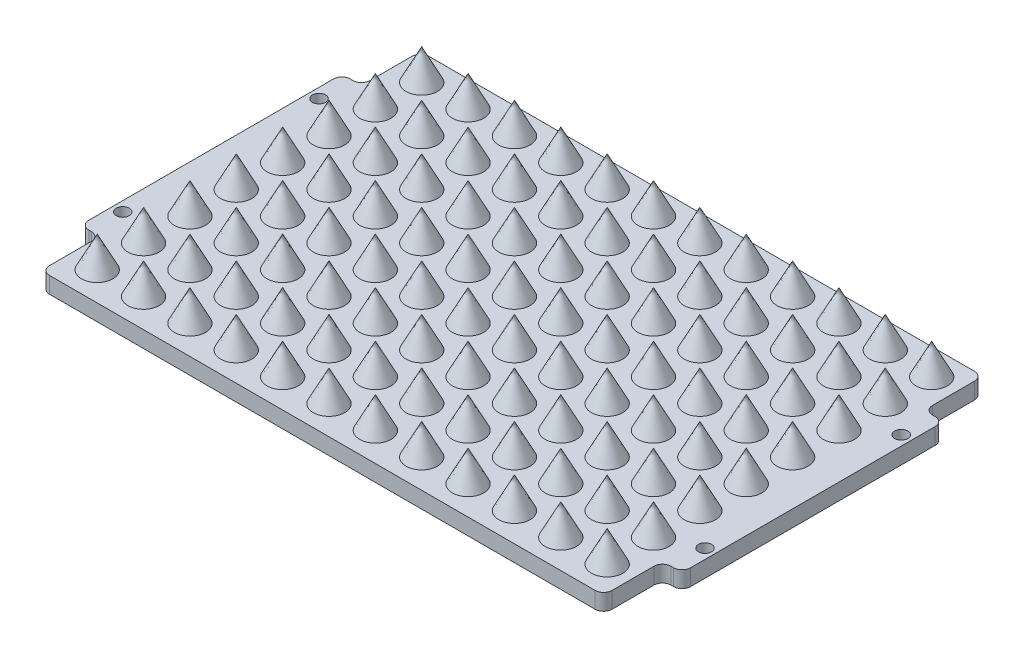
SolidWorks part; units mm, degrees
ref_plane "Front Plane" through (0, 0, 0) normal (0, 0, 1) x (1, 0, 0)
ref_plane "Top Plane" through (0, 0, 0) normal (0, 1, 0) x (1, 0, 0)
ref_plane "Right Plane" through (0, 0, 0) normal (1, 0, 0) x (0, 0, -1)
sketch "Sketch1" plane through (0, 0, 0) normal (0, 1, 0) x (1, 0, 0)
  line L1 (-54.61, -36.83) -> (54.61, -36.83)
  line L2 (-54.61, -36.83) -> (-54.61, 36.83)
  line L3 (-54.61, 36.83) -> (54.61, 36.83)
  line L4 (54.61, -36.83) -> (54.61, 36.83)
  line L5 (-54.61, -36.83) -> (54.61, 36.83) construction
  line L6 (-54.61, 36.83) -> (54.61, -36.83) construction
  point P0 (0, 0)
  dimension "D1" = 109.22
  dimension "D2" = 73.66
extrude "Boss-Extrude1" add sketch "Sketch1" against normal blind 3.175
ref_plane "Plane1" through (0, 0, -31.75) normal (0, 0, 1) x (1, 0, 0)
sketch "Sketch2" plane through (0, 0, -31.75) normal (0, 0, 1) x (1, 0, 0)
  line L0 (-52.324, 0) -> (-49.276, 6)
  line L3 (-49.276, 0) -> (-52.324, 0)
  line L4 (-49.276, 6) -> (-49.276, 0)
  point P5 (-50.8, 0)
  dimension "D1" = 3.048
  dimension "D3" = 50.8
revolve "Revolve3" add sketch "Sketch2" angle 360 about L4
pattern_linear "LPattern1" count 12 spacing 9 along (1, 0, 0) count 8 spacing 9 along (0, 0, 1) of "Revolve3"
sketch "Sketch3" plane through (0, 0, 0) normal (0, 1, 0) x (1, 0, 0)
  line L0 (-54.61, 36.83) -> (-54.61, -36.83) construction
  line L1 (-54.61, 25.4) -> (-58.42, 25.4)
  line L2 (-54.61, 25.4) -> (-54.61, -25.4)
  line L3 (-54.61, -25.4) -> (-58.42, -25.4)
  line L4 (-58.42, 25.4) -> (-58.42, -25.4)
  line L5 (0, 0) -> (0, 36.83) construction
  line L6 (54.61, 36.83) -> (-54.61, 36.83) construction
  line L7 (58.42, 25.4) -> (58.42, -25.4)
  line L8 (54.61, -25.4) -> (58.42, -25.4)
  line L9 (54.61, 25.4) -> (54.61, -25.4)
  line L10 (54.61, 25.4) -> (58.42, 25.4)
  circle A0 centre (-56.515, 19.05) radius 1.27
  circle A1 centre (-56.515, -19.05) radius 1.27
  circle A2 centre (56.515, -19.05) radius 1.27
  circle A3 centre (56.515, 19.05) radius 1.27
  point P6 (-58.42, 0)
  point P11 (-56.515, 25.4)
  dimension "D3" = 2.54
  dimension "D1" = 3.81
  dimension "D2" = 50.8
  dimension "D4" = 19.05
  dimension "D5" = 2
extrude "Boss-Extrude2" add sketch "Sketch3" against normal blind 3.175
fillet "Fillet1" radius 1.651 12 edges at (54.61, -1.5875, -36.83) (54.61, -1.5875, -25.4) (58.42, -1.5875, -25.4) (58.42, -1.5875, 25.4) (54.61, -1.5875, 25.4) (54.61, -1.5875, 36.83) (-54.61, -1.5875, 36.83) (-54.61, -1.5875, 25.4) (-58.42, -1.5875, 25.4) (-58.42, -1.5875, -25.4) (-54.61, -1.5875, -25.4) (-54.61, -1.5875, -36.83)
